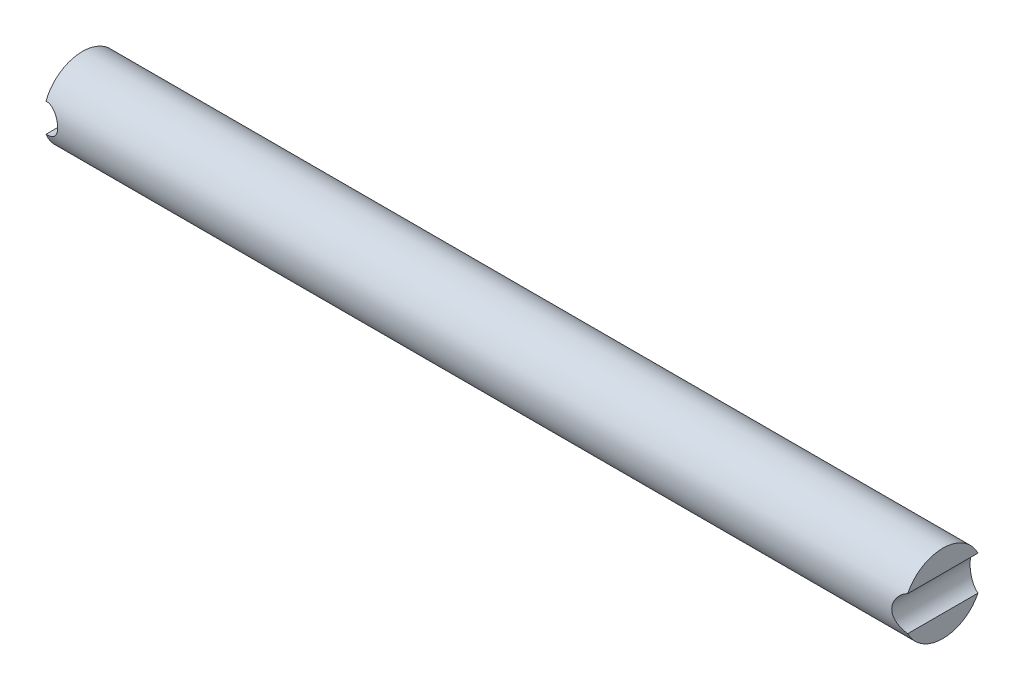
SolidWorks part; units mm, degrees
material "Legs"
ref_plane "Front Plane" through (0, 0, 0) normal (0, 0, 1) x (1, 0, 0)
ref_plane "Top Plane" through (0, 0, 0) normal (0, 1, 0) x (1, 0, 0)
ref_plane "Right Plane" through (0, 0, 0) normal (1, 0, 0) x (0, 0, -1)
sketch "Sketch1" plane through (0, 0, 0) normal (1, 0, 0) x (0, 0, -1)
  circle A0 centre (0, 0) radius 23
  dimension "D1" = 46
extrude "Length" add sketch "Sketch1" along normal blind 505
sketch "Sketch2" plane through (0, 0, 0) normal (0, 0, 1) x (1, 0, 0)
  circle A0 centre (0, 0) radius 8.4309
  circle A1 centre (508.8723, 0) radius 10.8771
extrude "Femur hole" cut sketch "Sketch2" against normal up to next and the other way up to next
